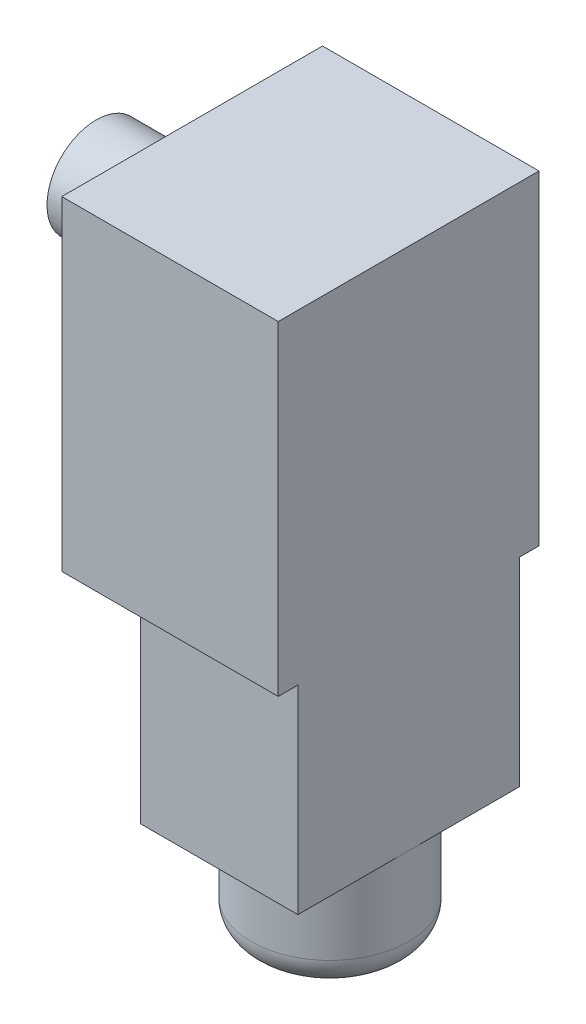
SolidWorks part; units mm, degrees
ref_plane "Plano frontal" through (0, 0, 0) normal (0, 0, 1) x (1, 0, 0)
ref_plane "Plano superior" through (0, 0, 0) normal (0, 1, 0) x (1, 0, 0)
ref_plane "Plano direito" through (0, 0, 0) normal (1, 0, 0) x (0, 0, -1)
sketch "Esboço1" plane through (0, 0, 0) normal (0, 0, 1) x (1, 0, 0)
  line L1 (-42.8288, -13.6718) -> (-22.8288, -13.6718)
  line L2 (-42.8288, -13.6718) -> (-42.8288, -77.8718)
  line L3 (-42.8288, -77.8718) -> (-22.8288, -77.8718)
  line L4 (-22.8288, -13.6718) -> (-22.8288, -77.8718)
  dimension "D1" = 64.2
  dimension "D2" = 20
extrude "Ressalto-extrusão1" add sketch "Esboço1" along normal blind 22.5
sketch "Esboço2" plane through (-42.8288, 0, 0) normal (-1, 0, 0) x (0, 0, 1)
  line L0 (0, -13.6718) -> (0, -77.8718) construction
  line L1 (22.5, -13.6718) -> (0, -13.6718)
  line L2 (22.5, -13.6718) -> (22.5, -46.6661)
  line L3 (22.5, -46.6661) -> (0, -46.6661)
  line L4 (0, -13.6718) -> (0, -46.6661)
extrude "Ressalto-extrusão2" add sketch "Esboço2" along normal blind 2
sketch "Esboço3" plane through (0, 0, 0) normal (0, 0, -1) x (-1, 0, 0)
  line L0 (22.8288, -77.8718) -> (22.8288, -13.6718) construction
  line L1 (44.8288, -13.6718) -> (22.8288, -13.6718)
  line L2 (44.8288, -13.6718) -> (44.8288, -46.6661)
  line L3 (44.8288, -46.6661) -> (22.8288, -46.6661)
  line L4 (22.8288, -13.6718) -> (22.8288, -46.6661)
extrude "Ressalto-extrusão3" add sketch "Esboço3" along normal blind 2
sketch "Esboço4" plane through (0, 0, 22.5) normal (0, 0, 1) x (1, 0, 0)
  line L2 (-44.8288, -46.6661) -> (-22.8288, -46.6661)
  line L3 (-44.8288, -46.6661) -> (-44.8288, -13.6718)
  line L4 (-44.8288, -13.6718) -> (-22.8288, -13.6718)
  line L5 (-22.8288, -46.6661) -> (-22.8288, -13.6718)
extrude "Ressalto-extrusão5" add sketch "Esboço4" along normal blind 2
sketch "Esboço5" plane through (-42.8288, 0, 0) normal (-1, 0, 0) x (0, 0, 1)
  line L1 (0, -46.6661) -> (22.5, -46.6661)
  line L2 (0, -46.6661) -> (0, -77.8718)
  line L3 (0, -77.8718) -> (22.5, -77.8718)
  line L4 (22.5, -46.6661) -> (22.5, -77.8718)
extrude "Corte-extrusão1" cut sketch "Esboço5" against normal blind 4
sketch "Esboço8" plane through (0, -46.6661, 0) normal (0, -1, 0) x (1, 0, 0)
  line L0 (-38.8288, 0) -> (-38.8288, 22.5)
  line L1 (-38.8288, 22.5) -> (-38.8288, 0) construction
  arc A0 (-38.8288, 0) -> (-38.8288, 22.5) centre (-27.5788, 11.25) cw
extrude "Ressalto-extrusão6" add sketch "Esboço8" along normal blind 20
sketch "Esboço9" plane through (0, -77.8718, 0) normal (0, -1, 0) x (-1, 0, 0)
  line L0 (38.8288, 0) -> (38.8288, -22.5)
  line L1 (38.8288, -22.5) -> (22.8288, -22.5)
  line L2 (22.8288, -22.5) -> (22.8288, 0)
  line L3 (22.8288, 0) -> (38.8288, 0)
  circle A0 centre (30.8288, -11.25) radius 8
  line M1 (38.8288, -22.5) -> (38.8288, 0)
  line M2 (38.8288, 0) -> (22.8288, 0)
  line M3 (22.8288, 0) -> (22.8288, -22.5)
  line M4 (22.8288, -22.5) -> (38.8288, -22.5)
extrude "Corte-extrusão2" cut sketch "Esboço9" against normal blind 11 contours A0 L2 M4 M1 | A0 L0 M2 M3
fillet "Filete1" radius 3 1 edges at (-30.8288, -77.8718, 3.25)
sketch "Esboço10" plane through (-44.8288, 0, 0) normal (-1, 0, 0) x (0, 0, 1)
  line L2 (-2, -46.6661) -> (-2, -13.6718) construction
  circle A0 centre (11, -23.6718) radius 5
  dimension "D1" = 10
  dimension "D2" = 10
  dimension "D3" = 13
extrude "Ressalto-extrusão7" add sketch "Esboço10" along normal blind 10
